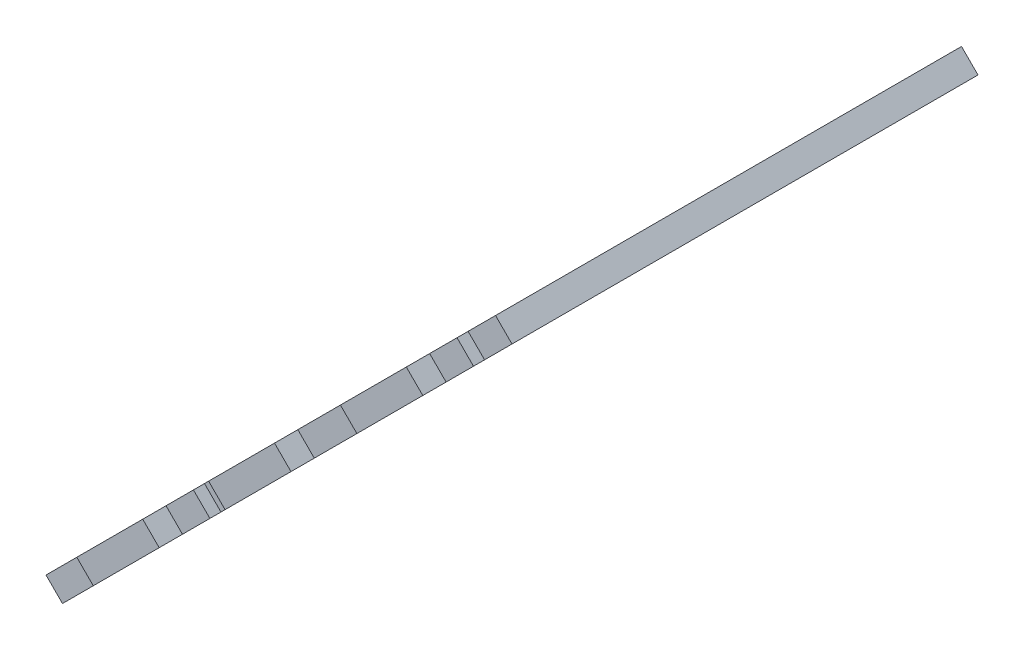
SolidWorks part; units mm, degrees
ref_plane "Front Plane" through (0, 0, 0) normal (0, 0, 1) x (1, 0, 0)
ref_plane "Top Plane" through (0, 0, 0) normal (0, 1, 0) x (1, 0, 0)
ref_plane "Right Plane" through (0, 0, 0) normal (1, 0, 0) x (0, 0, -1)
sketch "Sketch1" plane through (0, 0, 0) normal (0, 0, 1) x (1, 0, 0)
  line L0 (0, 127) -> (4.4901, 122.5099)
  line L1 (0, 127) -> (-122.5099, 4.4901)
  line L2 (4.4901, 122.5099) -> (-118.0197, 0)
  line L3 (-122.5099, 4.4901) -> (-118.0197, 0)
  line L4 (127, 0) -> (0, 127) construction
  line L5 (4.4901, -122.5099) -> (-122.5099, 4.4901) construction
  dimension "D1" = 6.35
extrude "Boss-Extrude1" add sketch "Sketch1" along normal up to surface (127 mm away)
sketch "Sketch2" plane through (-59.0099, -59.0099, 0) normal (-0.7071, -0.7071, 0) x (0, 0, 1)
  line L0 (127, 83.4526) -> (0, 83.4526) construction
  line L1 (25.4, 83.4526) -> (50.8, 83.4526)
  line L2 (25.4, 83.4526) -> (25.4, 89.8026)
  line L3 (25.4, 89.8026) -> (50.8, 89.8026)
  line L4 (50.8, 83.4526) -> (50.8, 89.8026)
  line L5 (127, 89.8026) -> (0, 89.8026) construction
  dimension "D1" = 25.4
  dimension "D2" = 25.4
extrude "Boss-Extrude2" add sketch "Sketch2" along normal blind 6.35
pattern_linear "LPattern1" count 2 spacing 50.8 along (0, 0, 1) of "Boss-Extrude2"
sketch "Sketch3" plane through (-59.0099, 59.0099, 0) normal (0.7071, -0.7071, 0) x (0, 0, -1)
  line L0 (-35.9664, -83.4526) -> (-40.2336, -89.8026) construction
  line L1 (-25.4, -89.8026) -> (-50.8, -89.8026) construction
  line L2 (-40.2336, -83.4526) -> (-40.2336, -89.8026) construction
  line L3 (-40.2336, -83.4526) -> (-35.9664, -89.8026) construction
  line L4 (-35.9664, -83.4526) -> (-35.9664, -89.8026) construction
  line L5 (-86.8461, -83.4526) -> (-91.1133, -89.8026) construction
  line L6 (-76.2, -89.8026) -> (-101.6, -89.8026) construction
  line L7 (-91.1133, -83.4526) -> (-91.1133, -89.8026) construction
  line L8 (-91.1133, -83.4526) -> (-86.8461, -89.8026) construction
  circle A0 centre (-38.1, -86.6276) radius 2.0955
  circle A1 centre (-88.9797, -86.6276) radius 2.0955
  dimension "D1" = 4.191
extrude "Cut-Extrude1" cut sketch "Sketch3" against normal blind 6.35
sketch "Sketch4" plane through (-63.5, 63.5, 0) normal (-0.7071, 0.7071, 0) x (0, 0, 1)
  line L0 (12.7, -83.4526) -> (12.7, -46.5697) construction
  line L1 (25.4, -83.4526) -> (0, -83.4526) construction
  line L2 (114.3, -83.4526) -> (114.3, -49.3378) construction
  line L3 (127, -83.4526) -> (101.6, -83.4526) construction
  line B0 (10.5664, -83.4526) -> (14.8336, -83.4526)
  line B1 (14.8336, -71.5146) -> (17.145, -71.5146)
  line B2 (17.145, -71.5146) -> (17.145, -74.6896)
  line B3 (17.145, -74.6896) -> (14.8336, -74.6896)
  line B4 (14.8336, -74.6896) -> (14.8336, -83.4526)
  line B5 (14.8336, -71.5146) -> (14.8336, -68.2126)
  line B6 (14.8336, -68.2126) -> (10.5664, -68.2126)
  line B7 (10.5664, -71.5146) -> (10.5664, -68.2126)
  line B8 (10.5664, -74.6896) -> (10.5664, -83.4526)
  line B9 (8.255, -74.6896) -> (10.5664, -74.6896)
  line B10 (8.255, -71.5146) -> (8.255, -74.6896)
  line B11 (10.5664, -71.5146) -> (8.255, -71.5146)
  line B12 (112.1664, -83.4526) -> (116.4336, -83.4526)
  line B13 (116.4336, -71.5146) -> (118.745, -71.5146)
  line B14 (118.745, -71.5146) -> (118.745, -74.6896)
  line B15 (118.745, -74.6896) -> (116.4336, -74.6896)
  line B16 (116.4336, -74.6896) -> (116.4336, -83.4526)
  line B17 (116.4336, -71.5146) -> (116.4336, -68.2126)
  line B18 (116.4336, -68.2126) -> (112.1664, -68.2126)
  line B19 (112.1664, -71.5146) -> (112.1664, -68.2126)
  line B20 (112.1664, -74.6896) -> (112.1664, -83.4526)
  line B21 (109.855, -74.6896) -> (112.1664, -74.6896)
  line B22 (109.855, -71.5146) -> (109.855, -74.6896)
  line B23 (112.1664, -71.5146) -> (109.855, -71.5146)
sketch_block_instance "TSlot-1"
sketch_block "TSlot" parameters "D1"=3.302, "D2"=3.175
sketch_block_instance "TSlot-3"
extrude "Cut-Extrude2" cut sketch "Sketch4" against normal blind 6.35
sketch "Sketch6" plane through (0, 0, 0) normal (0, 0, -1) x (-1, 0, 0)
  line L0 (13.4704, 104.5494) -> (17.9605, 109.0395)
  line L1 (118.0197, 0) -> (-4.4901, 122.5099) construction
  line L2 (0, 127) -> (122.5099, 4.4901) construction
  line L3 (17.9605, 109.0395) -> (35.921, 91.079)
  line L4 (35.921, 91.079) -> (31.4309, 86.5888)
  line L5 (31.4309, 86.5888) -> (13.4704, 104.5494)
  dimension "D1" = 25.4
  dimension "D2" = 25.4
extrude "Boss-Extrude4" add sketch "Sketch6" along normal blind 6.35
pattern_linear "LPattern3" count 3 spacing 50.8 along (-0.7071, -0.7071, 0) of "Boss-Extrude4"
sketch "Sketch7" plane through (0, 0, 127) normal (0, 0, 1) x (1, 0, 0)
  line L0 (-17.9605, 109.0395) -> (-13.4704, 104.5494)
  line L1 (-122.5099, 4.4901) -> (0, 127) construction
  line L2 (4.4901, 122.5099) -> (-118.0197, 0) construction
  line L3 (-13.4704, 104.5494) -> (-31.4309, 86.5888)
  line L4 (-31.4309, 86.5888) -> (-35.921, 91.079)
  line L5 (-35.921, 91.079) -> (-17.9605, 109.0395)
  dimension "D1" = 25.4
  dimension "D2" = 25.4
extrude "Boss-Extrude5" add sketch "Sketch7" along normal blind 6.35
pattern_linear "LPattern4" count 3 spacing 50.8 along (-0.7071, -0.7071, 0) of "Boss-Extrude5"
sketch "Sketch8" plane through (-63.5, 63.5, 0) normal (-0.7071, 0.7071, 0) x (0, 0, 1)
  line L0 (0, 89.8026) -> (0, 64.4026) construction
  line L1 (127, 89.8026) -> (127, 64.3838) construction
  line L2 (0, -24.4974) -> (10.2536, -24.4974) construction
  line L3 (0, -11.7974) -> (0, -37.1974) construction
  line L4 (0, 77.1026) -> (13.5818, 77.1026) construction
  line L5 (127, 77.1026) -> (104.4683, 77.1026) construction
  line L6 (127, 64.4026) -> (127, 89.8026) construction
  line L7 (127, -24.4974) -> (109.5887, -24.4974) construction
  line L8 (127, -37.1974) -> (127, -11.7974) construction
  line B0 (127, -26.631) -> (127, -22.3638)
  line B1 (115.062, -22.3638) -> (115.062, -20.0524)
  line B2 (115.062, -20.0524) -> (118.237, -20.0524)
  line B3 (118.237, -20.0524) -> (118.237, -22.3638)
  line B4 (118.237, -22.3638) -> (127, -22.3638)
  line B5 (115.062, -22.3638) -> (111.76, -22.3638)
  line B6 (111.76, -22.3638) -> (111.76, -26.631)
  line B7 (115.062, -26.631) -> (111.76, -26.631)
  line B8 (118.237, -26.631) -> (127, -26.631)
  line B9 (118.237, -28.9424) -> (118.237, -26.631)
  line B10 (115.062, -28.9424) -> (118.237, -28.9424)
  line B11 (115.062, -26.631) -> (115.062, -28.9424)
  line B12 (0, 79.2362) -> (0, 74.969)
  line B13 (11.938, 74.969) -> (11.938, 72.6576)
  line B14 (11.938, 72.6576) -> (8.763, 72.6576)
  line B15 (8.763, 72.6576) -> (8.763, 74.969)
  line B16 (8.763, 74.969) -> (0, 74.969)
  line B17 (11.938, 74.969) -> (15.24, 74.969)
  line B18 (15.24, 74.969) -> (15.24, 79.2362)
  line B19 (11.938, 79.2362) -> (15.24, 79.2362)
  line B20 (8.763, 79.2362) -> (0, 79.2362)
  line B21 (8.763, 81.5476) -> (8.763, 79.2362)
  line B22 (11.938, 81.5476) -> (8.763, 81.5476)
  line B23 (11.938, 79.2362) -> (11.938, 81.5476)
  line B24 (0, -22.3638) -> (0, -26.631)
  line B25 (11.938, -26.631) -> (11.938, -28.9424)
  line B26 (11.938, -28.9424) -> (8.763, -28.9424)
  line B27 (8.763, -28.9424) -> (8.763, -26.631)
  line B28 (8.763, -26.631) -> (0, -26.631)
  line B29 (11.938, -26.631) -> (15.24, -26.631)
  line B30 (15.24, -26.631) -> (15.24, -22.3638)
  line B31 (11.938, -22.3638) -> (15.24, -22.3638)
  line B32 (8.763, -22.3638) -> (0, -22.3638)
  line B33 (8.763, -20.0524) -> (8.763, -22.3638)
  line B34 (11.938, -20.0524) -> (8.763, -20.0524)
  line B35 (11.938, -22.3638) -> (11.938, -20.0524)
  line B36 (127, 74.969) -> (127, 79.2362)
  line B37 (115.062, 79.2362) -> (115.062, 81.5476)
  line B38 (115.062, 81.5476) -> (118.237, 81.5476)
  line B39 (118.237, 81.5476) -> (118.237, 79.2362)
  line B40 (118.237, 79.2362) -> (127, 79.2362)
  line B41 (115.062, 79.2362) -> (111.76, 79.2362)
  line B42 (111.76, 79.2362) -> (111.76, 74.969)
  line B43 (115.062, 74.969) -> (111.76, 74.969)
  line B44 (118.237, 74.969) -> (127, 74.969)
  line B45 (118.237, 72.6576) -> (118.237, 74.969)
  line B46 (115.062, 72.6576) -> (118.237, 72.6576)
  line B47 (115.062, 74.969) -> (115.062, 72.6576)
sketch_block_instance "TSlot-4"
sketch_block_instance "TSlot-5"
sketch_block_instance "TSlot-7"
sketch_block_instance "TSlot-8"
extrude "Cut-Extrude3" cut sketch "Sketch8" against normal blind 6.35
